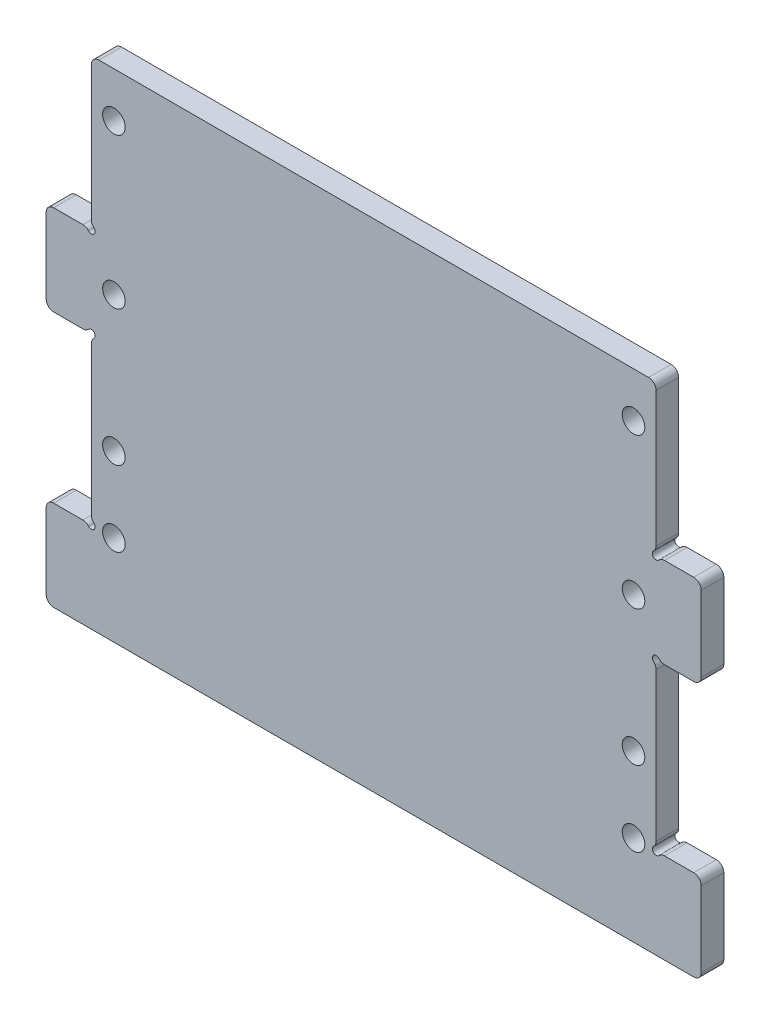
SolidWorks part; units mm, degrees
material "Thornel Mat VMA"
ref_plane "前视基准面" through (0, 0, 0) normal (0, 0, 1) x (1, 0, 0)
ref_plane "上视基准面" through (0, 0, 0) normal (0, 1, 0) x (1, 0, 0)
ref_plane "右视基准面" through (0, 0, 0) normal (1, 0, 0) x (0, 0, -1)
other "Configuration Table"
sketch "草图1" plane through (0, 0, 0) normal (0, 0, 1) x (1, 0, 0)
  line L0 (0, 0) -> (0, -10.6579) construction
  line L1 (-37.525, 39) -> (37.525, 39)
  line L2 (-37.525, 39) -> (-37.525, 19.5)
  line L3 (-37.525, -39) -> (37.525, -39)
  line L4 (37.525, 39) -> (37.525, 19.5)
  line L5 (-37.525, 39) -> (37.525, -39) construction
  line L6 (-37.525, -39) -> (37.525, 39) construction
  line L7 (-43.525, -27) -> (-37.525, -27)
  line L8 (43.525, 19) -> (38.025, 19)
  line L9 (43.525, 19) -> (43.525, 7)
  line L10 (43.525, 7) -> (38.025, 7)
  line L12 (43.525, 19) -> (37.525, 7) construction
  line L13 (43.525, 7) -> (37.525, 19) construction
  line L14 (43.525, -15) -> (38.025, -15)
  line L15 (43.525, -15) -> (43.525, -27)
  line L16 (43.525, -27) -> (37.525, -27)
  line L18 (43.525, -15) -> (37.525, -27) construction
  line L19 (43.525, -27) -> (37.525, -15) construction
  line L20 (-43.525, -15) -> (-43.525, -27)
  line L21 (-43.525, -15) -> (-38.025, -15)
  line L22 (-43.525, 19) -> (-43.525, 7)
  line L23 (-43.525, 19) -> (-38.025, 19)
  line L24 (-43.525, 7) -> (-38.025, 7)
  line L25 (37.525, 6.5) -> (37.525, -14.5)
  line L26 (37.525, -27) -> (37.525, -39)
  line L27 (-37.525, 6.5) -> (-37.525, -14.5)
  line L28 (-37.525, -27) -> (-37.525, -39)
  line L29 (37.525, -27) -> (-37.525, -27)
  circle A0 centre (-34.525, 33) radius 1.5
  circle A1 centre (-34.525, 13) radius 1.5
  circle A2 centre (-34.525, -5) radius 1.5
  circle A3 centre (-34.525, -15) radius 1.5
  circle A4 centre (34.525, 33) radius 1.5
  circle A5 centre (34.525, 13) radius 1.5
  circle A6 centre (34.525, -5) radius 1.5
  circle A7 centre (34.525, -15) radius 1.5
  arc A8 (37.525, 19.5) -> (38.025, 19) centre (37.525, 19) ccw
  arc A9 (38.025, 7) -> (37.525, 6.5) centre (37.525, 7) ccw
  arc A10 (37.525, -14.5) -> (38.025, -15) centre (37.525, -15) ccw
  arc A11 (-38.025, 19) -> (-37.525, 19.5) centre (-37.525, 19) ccw
  arc A12 (-37.525, 6.5) -> (-38.025, 7) centre (-37.525, 7) ccw
  arc A13 (-38.025, -15) -> (-37.525, -14.5) centre (-37.525, -15) ccw
  point P0 (0, 0)
  point P24 (40.525, 13)
  point P29 (40.525, -21)
  point P34 (40.775, 19)
  point P35 (40.775, -15)
  dimension "D3" = 3
  dimension "D4" = 6
  dimension "D5" = 20
  dimension "D6" = 3
  dimension "D7" = 18
  dimension "D8" = 10
  dimension "D15" = 1
  dimension "D1" = 75.05
  dimension "D2" = 78
  dimension "D9" = 20
  dimension "D10" = 22
  dimension "D11" = 12
  dimension "D12" = 12
  dimension "D13" = 6
  dimension "D14" = 6
extrude "凸台-拉伸1" add sketch "草图1" along normal blind 3 contours A13 L21 L20 L7 L29 L16 L15 L14 A10 L25 A9 L10 L9 L8 A8 L4 L1 L2 A11 L23 L22 L24 A12 L27 A6 A4 A3 A2 A1 A0 A5 A7
fillet "圆角1" radius 1 22 edges at (-37.525, -14.5, 1.5) (-43.525, 7, 1.5) (-43.525, 19, 1.5) (-38.025, 19, 1.5) (-37.525, 19.5, 1.5) (-37.525, 39, 1.5) (37.525, 39, 1.5) (37.525, 19.5, 1.5) (38.025, 19, 1.5) (43.525, 19, 1.5) (43.525, 7, 1.5) (38.025, 7, 1.5) (37.525, 6.5, 1.5) (37.525, -14.5, 1.5) (38.025, -15, 1.5) (43.525, -15, 1.5) (43.525, -27, 1.5) (-43.525, -27, 1.5) (-43.525, -15, 1.5) (-38.025, -15, 1.5) (-38.025, 7, 1.5) (-37.525, 6.5, 1.5)
